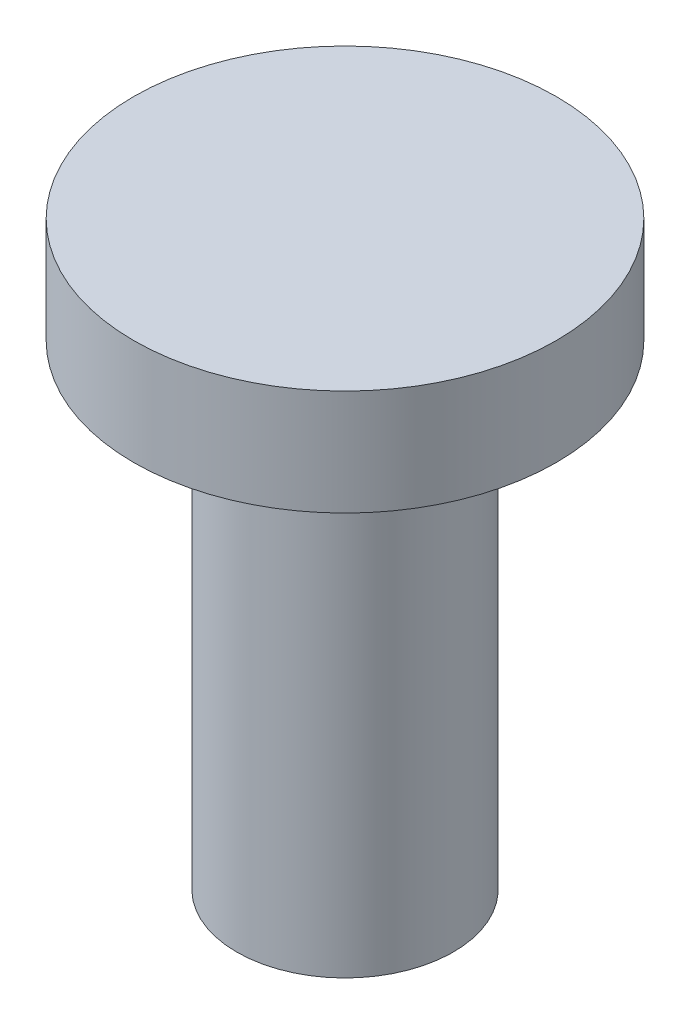
SolidWorks part; units mm, degrees
ref_plane "Front Plane" through (0, 0, 0) normal (0, 0, 1) x (1, 0, 0)
ref_plane "Top Plane" through (0, 0, 0) normal (0, 1, 0) x (1, 0, 0)
ref_plane "Right Plane" through (0, 0, 0) normal (1, 0, 0) x (0, 0, -1)
sketch "Sketch1" plane through (0, 0, 0) normal (0, 1, 0) x (1, 0, 0)
  circle A0 centre (0, 0) radius 1.025
extrude "Boss-Extrude1" add sketch "Sketch1" along normal blind 4.5
sketch "Sketch2" plane through (0, 4.5, 0) normal (0, 1, 0) x (1, 0, 0)
  circle A0 centre (0, 0) radius 2
extrude "Boss-Extrude2" add sketch "Sketch2" along normal blind 1
